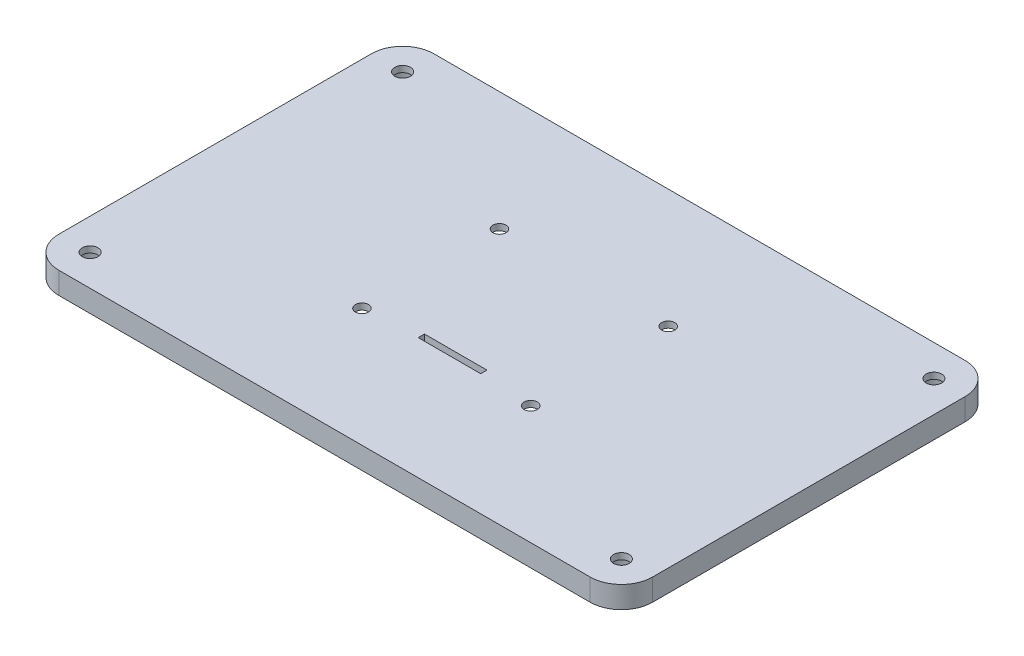
SolidWorks part; units mm, degrees
ref_plane "Front Plane" through (0, 0, 0) normal (0, 0, 1) x (1, 0, 0)
ref_plane "Top Plane" through (0, 0, 0) normal (0, 1, 0) x (1, 0, 0)
ref_plane "Right Plane" through (0, 0, 0) normal (1, 0, 0) x (0, 0, -1)
sketch "Sketch1" plane through (0, 111.7224, 0) normal (0, 1, 0) x (1, 0, 0)
  line L0 (249.4511, 952.2183) -> (249.4511, 944.7183)
  line L1 (241.9511, 959.7183) -> (234.4511, 959.7183)
  line L2 (404.4511, 952.2183) -> (404.4511, 944.7183)
  line L3 (411.9511, 959.7183) -> (419.4511, 959.7183)
  line L4 (241.9511, 942.2183) -> (411.9511, 942.2183)
  line L5 (421.9511, 952.2183) -> (421.9511, 1052.2183)
  line L6 (411.9511, 1062.2183) -> (241.9511, 1062.2183)
  line L7 (231.9511, 1052.2183) -> (231.9511, 952.2183)
  line L8 (241.9511, 942.2183) -> (411.9511, 942.2183)
  line L9 (421.9511, 952.2183) -> (421.9511, 1052.2183)
  line L10 (411.9511, 1062.2183) -> (241.9511, 1062.2183)
  line L11 (231.9511, 1052.2183) -> (231.9511, 952.2183)
  line L12 (249.4511, 944.7183) -> (404.4511, 944.7183)
  line L17 (419.4511, 959.7183) -> (419.4511, 1044.7183)
  line L18 (404.4511, 1059.7183) -> (249.4511, 1059.7183)
  line L19 (234.4511, 1044.7183) -> (234.4511, 959.7183)
  line L20 (411.9511, 1044.7183) -> (419.4511, 1044.7183)
  line L22 (326.9511, 942.2183) -> (326.9511, 1097.1265) construction
  line L23 (231.9511, 1002.2183) -> (434.7036, 1002.2183) construction
  line L26 (404.4511, 1052.2183) -> (404.4511, 1059.7183)
  line L27 (241.9511, 1044.7183) -> (234.4511, 1044.7183)
  line L28 (249.4511, 1052.2183) -> (249.4511, 1059.7183)
  line L29 (234.4511, 1052.2183) -> (234.4511, 952.2183) construction
  line L30 (411.9511, 1059.7183) -> (241.9511, 1059.7183) construction
  line L31 (241.9511, 944.7183) -> (411.9511, 944.7183) construction
  line L32 (419.4511, 952.2183) -> (419.4511, 1052.2183) construction
  arc A4 (411.9511, 942.2183) -> (421.9511, 952.2183) centre (411.9511, 952.2183) ccw
  arc A5 (421.9511, 1052.2183) -> (411.9511, 1062.2183) centre (411.9511, 1052.2183) ccw
  arc A6 (241.9511, 1062.2183) -> (231.9511, 1052.2183) centre (241.9511, 1052.2183) ccw
  arc A7 (231.9511, 952.2183) -> (241.9511, 942.2183) centre (241.9511, 952.2183) ccw
  arc A8 (411.9511, 942.2183) -> (421.9511, 952.2183) centre (411.9511, 952.2183) ccw
  arc A9 (421.9511, 1052.2183) -> (411.9511, 1062.2183) centre (411.9511, 1052.2183) ccw
  arc A10 (241.9511, 1062.2183) -> (231.9511, 1052.2183) centre (241.9511, 1052.2183) ccw
  arc A11 (231.9511, 952.2183) -> (241.9511, 942.2183) centre (241.9511, 952.2183) ccw
  circle A16 centre (241.9511, 952.2183) radius 5.5
  circle A17 centre (411.9511, 952.2183) radius 5.5
  circle A18 centre (411.9511, 1052.2183) radius 5.5
  circle A19 centre (241.9511, 1052.2183) radius 5.5
  arc A20 (249.4511, 952.2183) -> (241.9511, 959.7183) centre (241.9511, 952.2183) ccw
  arc A21 (411.9511, 959.7183) -> (404.4511, 952.2183) centre (411.9511, 952.2183) ccw
  arc A22 (404.4511, 1052.2183) -> (411.9511, 1044.7183) centre (411.9511, 1052.2183) ccw
  arc A23 (241.9511, 1044.7183) -> (249.4511, 1052.2183) centre (241.9511, 1052.2183) ccw
  arc A24 (241.9511, 1059.7183) -> (234.4511, 1052.2183) centre (241.9511, 1052.2183) ccw construction
  arc A25 (234.4511, 952.2183) -> (241.9511, 944.7183) centre (241.9511, 952.2183) ccw construction
  arc A26 (419.4511, 1052.2183) -> (411.9511, 1059.7183) centre (411.9511, 1052.2183) ccw construction
  arc A27 (411.9511, 944.7183) -> (419.4511, 952.2183) centre (411.9511, 952.2183) ccw construction
  dimension "D2" = 2.5
  dimension "D3" = 11
  dimension "D1" = 0
extrude "Boss-Extrude1" add sketch "Sketch1" along normal up to surface (5 mm away)
sketch "Sketch2" plane through (0, 116.7224, 0) normal (0, 1, 0) x (1, 0, 0)
  line L4 (231.9511, 1052.2183) -> (231.9511, 952.2183)
  line L5 (241.9511, 942.2183) -> (411.9511, 942.2183)
  line L6 (421.9511, 952.2183) -> (421.9511, 1052.2183)
  line L7 (411.9511, 1062.2183) -> (241.9511, 1062.2183)
  line L8 (231.9511, 1052.2183) -> (231.9511, 952.2183)
  line L9 (241.9511, 942.2183) -> (411.9511, 942.2183)
  line L10 (421.9511, 952.2183) -> (421.9511, 1052.2183)
  line L11 (411.9511, 1062.2183) -> (241.9511, 1062.2183)
  arc A4 (231.9511, 952.2183) -> (241.9511, 942.2183) centre (241.9511, 952.2183) ccw
  arc A5 (411.9511, 942.2183) -> (421.9511, 952.2183) centre (411.9511, 952.2183) ccw
  arc A6 (421.9511, 1052.2183) -> (411.9511, 1062.2183) centre (411.9511, 1052.2183) ccw
  arc A7 (241.9511, 1062.2183) -> (231.9511, 1052.2183) centre (241.9511, 1052.2183) ccw
  arc A8 (231.9511, 952.2183) -> (241.9511, 942.2183) centre (241.9511, 952.2183) ccw
  arc A9 (411.9511, 942.2183) -> (421.9511, 952.2183) centre (411.9511, 952.2183) ccw
  arc A10 (421.9511, 1052.2183) -> (411.9511, 1062.2183) centre (411.9511, 1052.2183) ccw
  arc A11 (241.9511, 1062.2183) -> (231.9511, 1052.2183) centre (241.9511, 1052.2183) ccw
  dimension "D1" = 0
extrude "Boss-Extrude2" add sketch "Sketch2" along normal blind 2
sketch "Sketch4" plane through (0, 118.7224, 0) normal (0, 1, 0) x (1, 0, 0)
  line L1 (375.8652, 1031.6724) -> (399.8652, 1031.6724)
  line L2 (375.8652, 1031.6724) -> (375.8652, 1007.6724)
  line L3 (375.8652, 1007.6724) -> (399.8652, 1007.6724)
  line L4 (399.8652, 1031.6724) -> (399.8652, 1007.6724)
  circle A0 centre (375.8652, 1031.6724) radius 1.4
  circle A1 centre (399.8652, 1031.6724) radius 1.4
  circle A4 centre (375.8652, 1007.6724) radius 1.4
  circle A5 centre (399.8652, 1007.6724) radius 1.4
  dimension "D3" = 2.8
  dimension "D1" = 24
  dimension "D2" = 24
extrude "Boss-Extrude3" add sketch "Sketch4" against normal blind 7 contours L1 A0 L2 | L2 A0 L1 | L2 A4 L3 | L3 A4 L2 | A1 | A5
sketch "Sketch10" plane through (0, 118.7224, 0) normal (0, 1, 0) x (1, 0, 0)
  line L0 (231.9511, 1002.2183) -> (421.9511, 1002.2183) construction
  line L1 (231.9511, 1052.2183) -> (231.9511, 952.2183) construction
  line L2 (421.9511, 952.2183) -> (421.9511, 1052.2183) construction
  line L3 (326.9511, 1062.2183) -> (326.9511, 942.2183) construction
  line L4 (411.9511, 1062.2183) -> (241.9511, 1062.2183) construction
  line L5 (241.9511, 942.2183) -> (411.9511, 942.2183) construction
sketch "Sketch12" plane through (0, 118.7224, 0) normal (0, 1, 0) x (1, 0, 0)
  line L0 (326.9511, 1062.2183) -> (326.9511, 942.2183) construction
  line L1 (318.1088, 983.0453) -> (338.1088, 983.0453)
  line L2 (318.1088, 983.0453) -> (318.1088, 981.0453)
  line L3 (318.1088, 981.0453) -> (338.1088, 981.0453)
  line L4 (338.1088, 983.0453) -> (338.1088, 981.0453)
  line L5 (411.9511, 1062.2183) -> (241.9511, 1062.2183) construction
  line L6 (241.9511, 942.2183) -> (411.9511, 942.2183) construction
extrude "Cut-Extrude1" cut sketch "Sketch12" against normal blind 10
hole_wizard "Ø4.2 (4.2) Diameter Hole1" positions "Sketch13" profile "Sketch14" hole size "Ø4.2" standard "ISO"
sketch "Sketch13" plane through (0, 118.7224, 0) normal (0, 1, 0) x (1, 0, 0)
  point P0 (300.991, 1024.1708)
  point P3 (354.991, 1024.1708)
  point P6 (354.991, 980.1708)
  point P9 (300.991, 980.1708)
sketch "Sketch14" plane through (300.991, 118.7224, -1024.1708) normal (1, 0, 0) x (0, 0, 1)
  line L0 (0, 0) -> (0, 21.2618)
  line L1 (0, 21.2618) -> (2.1, 20)
  line L2 (2.1, 20) -> (2.1, 0)
  line L5 (2.1, 0) -> (0, 0)
  line L10 (0, 21.2618) -> (-2.1, 20) construction
  line L11 (0, -6.35) -> (0, 107.95) construction
  dimension "Hole Dia." = 4.2
  dimension "Hole Depth" = 20
  dimension "Drill Angle" = 118
hole_wizard "Ø5.0 (5) Diameter Hole1" positions "Sketch18" profile "Sketch19" hole size "Ø5.0" standard "ISO"
sketch "Sketch18" plane through (0, 118.7224, 0) normal (0, 1, 0) x (1, 0, 0)
  point P3 (241.9511, 1052.2183)
  point P6 (411.9511, 1052.2183)
  point P9 (411.9511, 952.2183)
  point P12 (241.9511, 952.2183)
sketch "Sketch19" plane through (241.9511, 118.7224, -1052.2183) normal (1, 0, 0) x (0, 0, 1)
  line L0 (0, 0) -> (0, 6.5022)
  line L1 (0, 6.5022) -> (2.5, 5)
  line L2 (2.5, 5) -> (2.5, 0)
  line L5 (2.5, 0) -> (0, 0)
  line L10 (0, 6.5022) -> (-2.5, 5) construction
  line L11 (0, -6.35) -> (0, 107.95) construction
  dimension "Hole Dia." = 5
  dimension "Hole Depth" = 5
  dimension "Drill Angle" = 118
